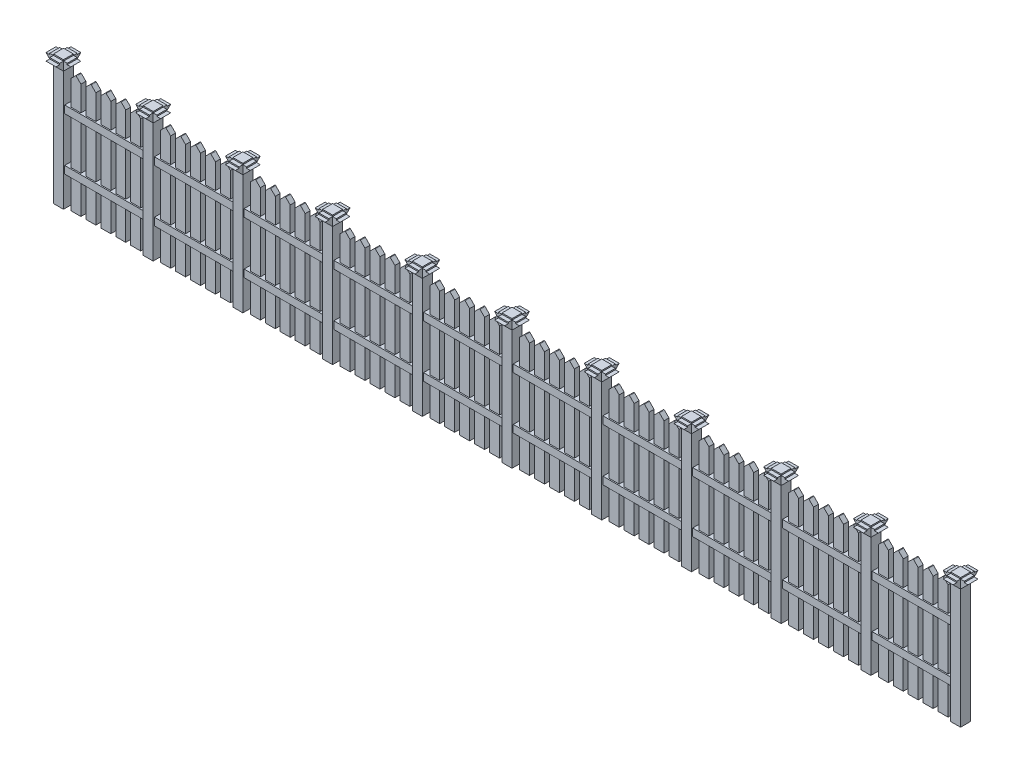
SolidWorks part; units mm, degrees
ref_plane "Front Plane" through (0, 0, 0) normal (0, 0, 1) x (1, 0, 0)
ref_plane "Top Plane" through (0, 0, 0) normal (0, 1, 0) x (1, 0, 0)
ref_plane "Right Plane" through (0, 0, 0) normal (1, 0, 0) x (0, 0, -1)
sketch "Sketch1" plane through (0, 0, 0) normal (0, 1, 0) x (1, 0, 0)
  line L1 (0, 0) -> (101.6, 0)
  line L2 (0, 0) -> (0, 101.6)
  line L3 (0, 101.6) -> (101.6, 101.6)
  line L4 (101.6, 0) -> (101.6, 101.6)
  dimension "D1" = 101.6
  dimension "D2" = 101.6
extrude "Boss-Extrude1" add sketch "Sketch1" along normal blind 1219.2
sketch "Sketch2" plane through (0, 0, 0) normal (0, 0, 1) x (1, 0, 0)
  line L0 (101.6, 1219.2) -> (177.8, 1295.4)
  line L1 (177.8, 1295.4) -> (139.7, 1295.4)
  line L2 (139.7, 1295.4) -> (139.7, 1308.1)
  line L3 (139.7, 1308.1) -> (101.6, 1308.1)
  line L4 (101.6, 1308.1) -> (101.6, 1320.8)
  line L5 (101.6, 1320.8) -> (0, 1320.8)
  line L6 (0, 1320.8) -> (0, 1308.1)
  line L7 (0, 1308.1) -> (-38.1, 1308.1)
  line L8 (-38.1, 1308.1) -> (-38.1, 1295.4)
  line L9 (-38.1, 1295.4) -> (-76.2, 1295.4)
  line L10 (-76.2, 1295.4) -> (0, 1219.2)
  line L11 (0, 1219.2) -> (101.6, 1219.2) construction
  line L12 (101.6, 1219.2) -> (101.6, 0) construction
  line L13 (0, 1219.2) -> (101.6, 1219.2)
  dimension "D1" = 135
  dimension "D2" = 135
  dimension "D3" = 101.6
  dimension "D4" = 38.1
  dimension "D5" = 38.1
  dimension "D6" = 38.1
  dimension "D7" = 38.1
  dimension "D8" = 12.7
  dimension "D9" = 12.7
  dimension "D10" = 12.7
extrude "Boss-Extrude2" add sketch "Sketch2" against normal blind 101.6
sketch "Sketch3" plane through (0, 0, 0) normal (1, 0, 0) x (0, 0, -1)
  line L0 (0, 1219.2) -> (-76.2, 1295.4)
  line L1 (-76.2, 1295.4) -> (-38.1, 1295.4)
  line L2 (-38.1, 1295.4) -> (-38.1, 1308.1)
  line L6 (0, 1308.1) -> (0, 1219.2)
  line L7 (0, 1308.1) -> (-38.1, 1308.1)
  dimension "D1" = 38.1
  dimension "D2" = 38.1
  dimension "D3" = 76.2
extrude "Boss-Extrude3" add sketch "Sketch3" along normal blind 101.6
ref_plane "Midplane" through (0, 0, -50.8) normal (0, 0, 1) x (1, 0, 0)
mirror "Mirror1" about plane through (0, 0, -50.8) normal (0, 0, 1) of "Boss-Extrude3"
sketch "Sketch4" plane through (0, 0, -50.8) normal (0, 0, 1) x (1, 0, 0)
  line L0 (152.4, 0) -> (152.4, 1219.2)
  line L1 (152.4, 1219.2) -> (254, 1219.2)
  line L2 (254, 1219.2) -> (254, 0)
  line L3 (254, 0) -> (152.4, 0)
  line L5 (0, 0) -> (101.6, 0) construction
  line L6 (101.6, 1219.2) -> (101.6, 0) construction
  point P6 (0, 0)
  dimension "D1" = 101.6
  dimension "D2" = 50.8
  dimension "D3" = 1219.2
extrude "Boss-Extrude4" add sketch "Sketch4" along normal mid plane 50.8 separate body
sketch "Sketch5" plane through (0, 0, -25.4) normal (0, 0, 1) x (1, 0, 0)
  line L0 (254, 1219.2) -> (152.4, 1219.2) construction
  line L1 (203.2, 1219.2) -> (152.4, 1168.4)
  line L2 (152.4, 1219.2) -> (152.4, 0) construction
  line L3 (152.4, 1168.4) -> (152.4, 1219.2)
  line L4 (152.4, 1219.2) -> (203.2, 1219.2)
  point P0 (203.2, 1219.2)
  dimension "D1" = 135
extrude "Cut-Extrude2" cut sketch "Sketch5" against normal blind 50.8
sketch "Sketch6" plane through (0, 0, -25.4) normal (0, 0, 1) x (1, 0, 0)
  line L0 (203.2, 1219.2) -> (254, 1168.4)
  line L1 (254, 0) -> (254, 1219.2) construction
  line L2 (254, 1168.4) -> (254, 1219.2)
  line L3 (254, 1219.2) -> (203.2, 1219.2)
  dimension "D1" = 45
extrude "Cut-Extrude3" cut sketch "Sketch6" against normal blind 50.8
sketch "Sketch7" plane through (0, 0, -25.4) normal (0, 0, 1) x (1, 0, 0)
  line L0 (203.2, 1219.2) -> (254, 1168.4) construction
  line L1 (152.4, 1168.4) -> (203.2, 1219.2) construction
  line L2 (203.2, 1219.2) -> (207.6901, 1214.7099)
  line L3 (198.7099, 1214.7099) -> (203.2, 1219.2)
  arc A0 (207.6901, 1214.7099) -> (198.7099, 1214.7099) centre (203.2, 1210.2197) ccw
  dimension "D1" = 12.7
extrude "Cut-Extrude4" cut sketch "Sketch7" against normal blind 50.8
sketch "Sketch8" plane through (101.6, 0, 0) normal (1, 0, 0) x (0, 0, -1)
  line L0 (0, 1219.2) -> (0, 0) construction
  line L1 (12.7, 304.8) -> (88.9, 304.8)
  line L2 (12.7, 304.8) -> (12.7, 381)
  line L3 (12.7, 381) -> (88.9, 381)
  line L4 (88.9, 304.8) -> (88.9, 381)
  line L5 (0, 0) -> (101.6, 0) construction
  dimension "D1" = 12.7
  dimension "D2" = 76.2
  dimension "D3" = 76.2
  dimension "D4" = 304.8
sketch "Sketch9" plane through (101.6, 0, 0) normal (1, 0, 0) x (0, 0, -1)
  line L0 (0, 1219.2) -> (101.6, 1219.2) construction
  line L1 (12.7, 838.2) -> (88.9, 838.2)
  line L2 (12.7, 838.2) -> (12.7, 914.4)
  line L3 (12.7, 914.4) -> (88.9, 914.4)
  line L4 (88.9, 838.2) -> (88.9, 914.4)
  line L5 (0, 1219.2) -> (0, 0) construction
  dimension "D1" = 304.8
  dimension "D2" = 76.2
  dimension "D3" = 12.7
  dimension "D4" = 76.2
extrude "Boss-Extrude7" add sketch "Sketch8" along normal blind 812.8 separate body
extrude "Boss-Extrude8" add sketch "Sketch9" along normal blind 812.8 separate body
pattern_linear "LPattern25" count 5 spacing 152.4 along (1, 0, 0) of "Boss-Extrude4", "Cut-Extrude2", "Cut-Extrude3", "Cut-Extrude4"
combine bodies "Combine1" operation type add bodies to combine 120 190 191 194 198 199 200
pattern_linear "LPattern30" count 11 spacing 914.4 along (1, 0, 0) of bodies 201 104
delete or keep bodies "Body-Delete/Keep 2" type delete bodies bodies 228
